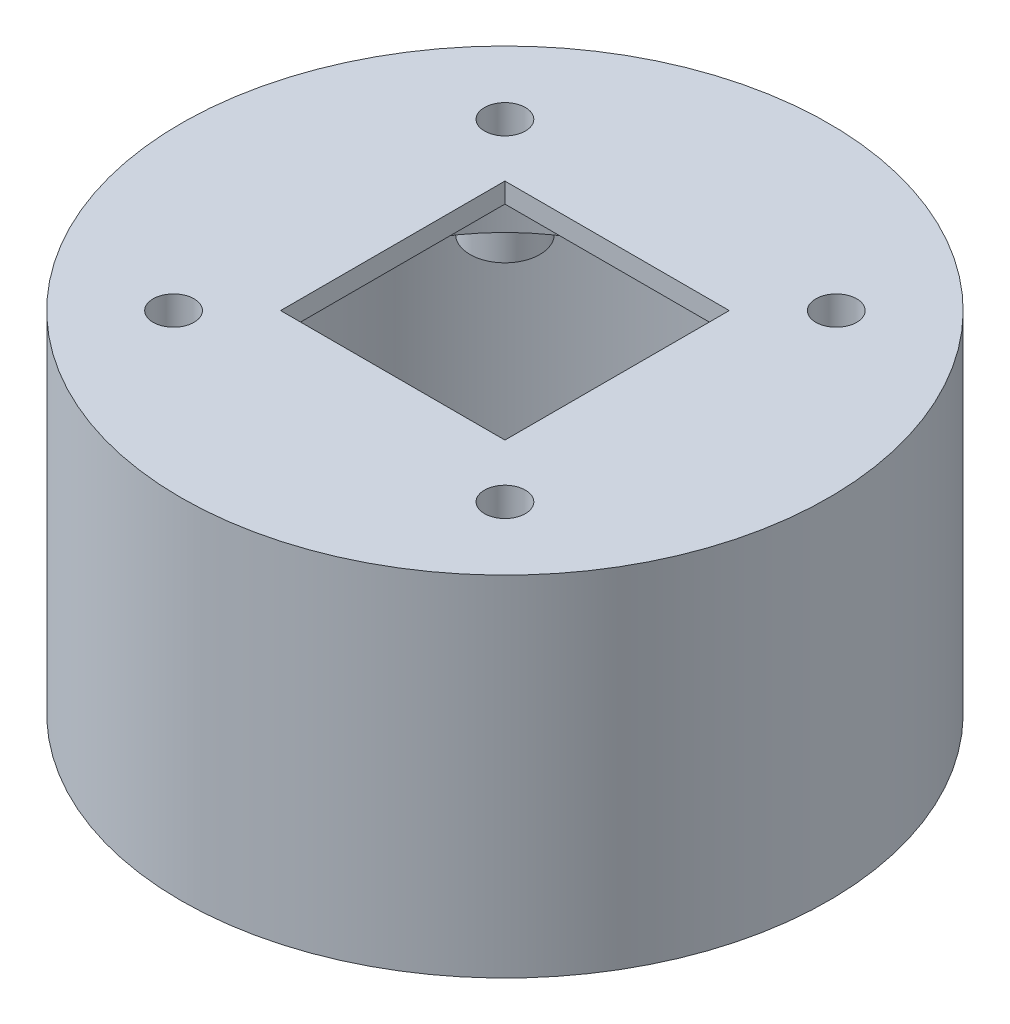
SolidWorks part; units mm, degrees
ref_plane "Спереди" through (0, 0, 0) normal (0, 0, 1) x (1, 0, 0)
ref_plane "Сверху" through (0, 0, 0) normal (0, 1, 0) x (1, 0, 0)
ref_plane "Справа" through (0, 0, 0) normal (1, 0, 0) x (0, 0, -1)
sketch "Sketch1" plane through (0, 0, 0) normal (0, 1, 0) x (1, 0, 0)
  circle A0 centre (0, 0) radius 60
  circle A1 centre (0, 0) radius 65
  dimension "D1" = 120
  dimension "D2" = 130
extrude "Boss-Extrude1" add sketch "Sketch1" along normal blind 50
sketch "Sketch2" plane through (0, 50, 0) normal (0, 1, 0) x (1, 0, 0)
  circle A0 centre (0, 0) radius 65
  circle A1 centre (0, 0) radius 65 construction
extrude "Boss-Extrude2" add sketch "Sketch2" along normal blind 20
sketch "Sketch3" plane through (0, 70, 0) normal (0, 1, 0) x (1, 0, 0)
  line L1 (33.234, 33.234) -> (-33.234, 33.234) construction
  line L2 (33.234, 33.234) -> (33.234, -33.234) construction
  line L3 (33.234, -33.234) -> (-33.234, -33.234) construction
  line L4 (-33.234, 33.234) -> (-33.234, -33.234) construction
  line L5 (33.234, 33.234) -> (-33.234, -33.234) construction
  line L6 (33.234, -33.234) -> (-33.234, 33.234) construction
  line L7 (22.5, 22.5) -> (-22.5, 22.5)
  line L8 (22.5, 22.5) -> (22.5, -22.5)
  line L9 (22.5, -22.5) -> (-22.5, -22.5)
  line L10 (-22.5, 22.5) -> (-22.5, -22.5)
  line L11 (22.5, 22.5) -> (-22.5, -22.5) construction
  line L12 (22.5, -22.5) -> (-22.5, 22.5) construction
  circle A0 centre (0, 0) radius 47 construction
  circle A1 centre (-33.234, -33.234) radius 4.1
  circle A2 centre (-33.234, 33.234) radius 4.1
  circle A3 centre (33.234, 33.234) radius 4.1
  circle A4 centre (33.234, -33.234) radius 4.1
  dimension "D1" = 94
  dimension "D2" = 8.2
  dimension "D3" = 45
extrude "Cut-Extrude1" cut sketch "Sketch3" against normal through all
sketch "Sketch5" plane through (0, 50, 0) normal (0, -1, 0) x (1, 0, 0)
  line L0 (0, 22.5) -> (0, 60) construction
  line L1 (-22.5, 22.5) -> (22.5, 22.5) construction
  line L3 (-22.5, 47.5) -> (22.5, 47.5)
  line L4 (-22.5, 47.5) -> (-22.5, 22.5)
  line L5 (-22.5, 22.5) -> (22.5, 22.5)
  line L6 (22.5, 47.5) -> (22.5, 22.5)
  line L7 (-22.5, 47.5) -> (22.5, 22.5) construction
  line L8 (-22.5, 22.5) -> (22.5, 47.5) construction
  circle A0 centre (0, 0) radius 60 construction
  point P7 (0, 35)
  dimension "D1" = 25
extrude "Cut-Extrude2" cut sketch "Sketch5" against normal blind 15
sketch "Sketch6" plane through (0, 50, 0) normal (0, -1, 0) x (1, 0, 0)
  circle A0 centre (0, 0) radius 50
  dimension "D1" = 100
extrude "Cut-Extrude3" cut sketch "Sketch6" against normal blind 6
sketch "Sketch7" plane through (0, 56, 0) normal (0, -1, 0) x (1, 0, 0)
  circle A0 centre (-33.234, -33.234) radius 7
  circle A1 centre (-33.234, 33.234) radius 7
  circle A2 centre (-33.234, 33.234) radius 4.1
  circle A3 centre (-33.234, -33.234) radius 4.1
  circle A4 centre (33.234, -33.234) radius 4.1
  circle A5 centre (33.234, 33.234) radius 4.1
  circle A6 centre (33.234, -33.234) radius 7
  circle A7 centre (33.234, 33.234) radius 7
  dimension "D1" = 14
extrude "Boss-Extrude3" add sketch "Sketch7" along normal up to surface (6 mm away) up to face at (0, 50, 19.2743)
sketch "Sketch8" plane through (0, 56, 0) normal (0, -1, 0) x (1, 0, 0)
  circle A0 centre (0, 0) radius 39
  dimension "D1" = 78
extrude "Cut-Extrude4" cut sketch "Sketch8" against normal blind 10
